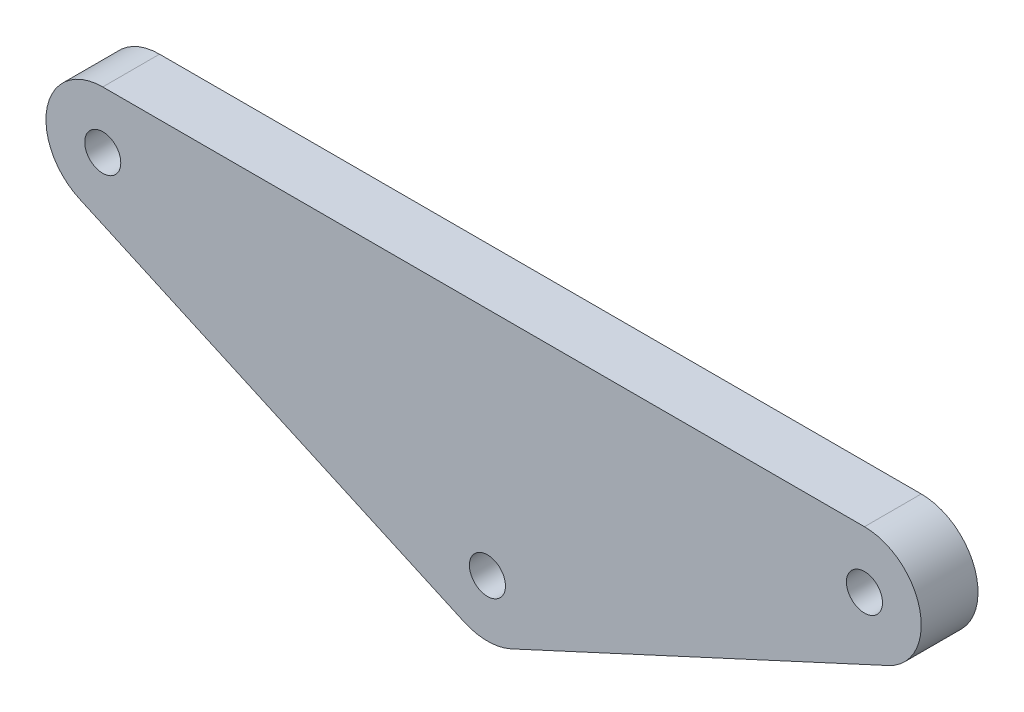
SolidWorks part; units mm, degrees
ref_plane "Front Plane" through (0, 0, 0) normal (0, 0, 1) x (1, 0, 0)
ref_plane "Top Plane" through (0, 0, 0) normal (0, 1, 0) x (1, 0, 0)
ref_plane "Right Plane" through (0, 0, 0) normal (1, 0, 0) x (0, 0, -1)
sketch "Sketch1" plane through (0, 0, 0) normal (0, 0, 1) x (1, 0, 0)
  line L3 (-33.54, 5) -> (33.54, 5)
  line L4 (-1.7232, -19.885) -> (-35.6013, -4.5553)
  line L5 (2.434, -19.8692) -> (35.6359, -4.5395)
  arc A3 (-33.54, 5) -> (-35.6013, -4.5553) centre (-33.54, 0) ccw
  arc A4 (33.54, 5) -> (35.6359, -4.5395) centre (33.54, 0) cw
  arc A5 (-1.7232, -19.885) -> (2.434, -19.8692) centre (0.3381, -15.3297) ccw
  point P0 (-33.54, 0)
  point P1 (33.54, 0)
  point P3 (0.3381, -15.3297)
  point P12 (0, 0)
  point P14 (0, 0)
  point P15 (0, 0)
  point P16 (0, 5)
  point P17 (0, 0)
  point P20 (-31.3113, -7.4628)
  dimension "D4" = 5
  dimension "D1" = 67.08
  dimension "D2" = 37.185
  dimension "D3" = 36.57
extrude "Boss-Extrude1" add sketch "Sketch1" along normal mid plane 5
sketch "Sketch2" plane through (0, 0, 2.5) normal (0, 0, 1) x (1, 0, 0)
  circle A0 centre (-33.54, 0) radius 1.5875
  circle A1 centre (33.54, 0) radius 1.5875
  circle A2 centre (0.3381, -15.3297) radius 1.5875
  point P6 (0, 0)
  point P8 (0, 0)
  dimension "D1" = 3.175
extrude "Cut-Extrude1" cut sketch "Sketch2" against normal through all
